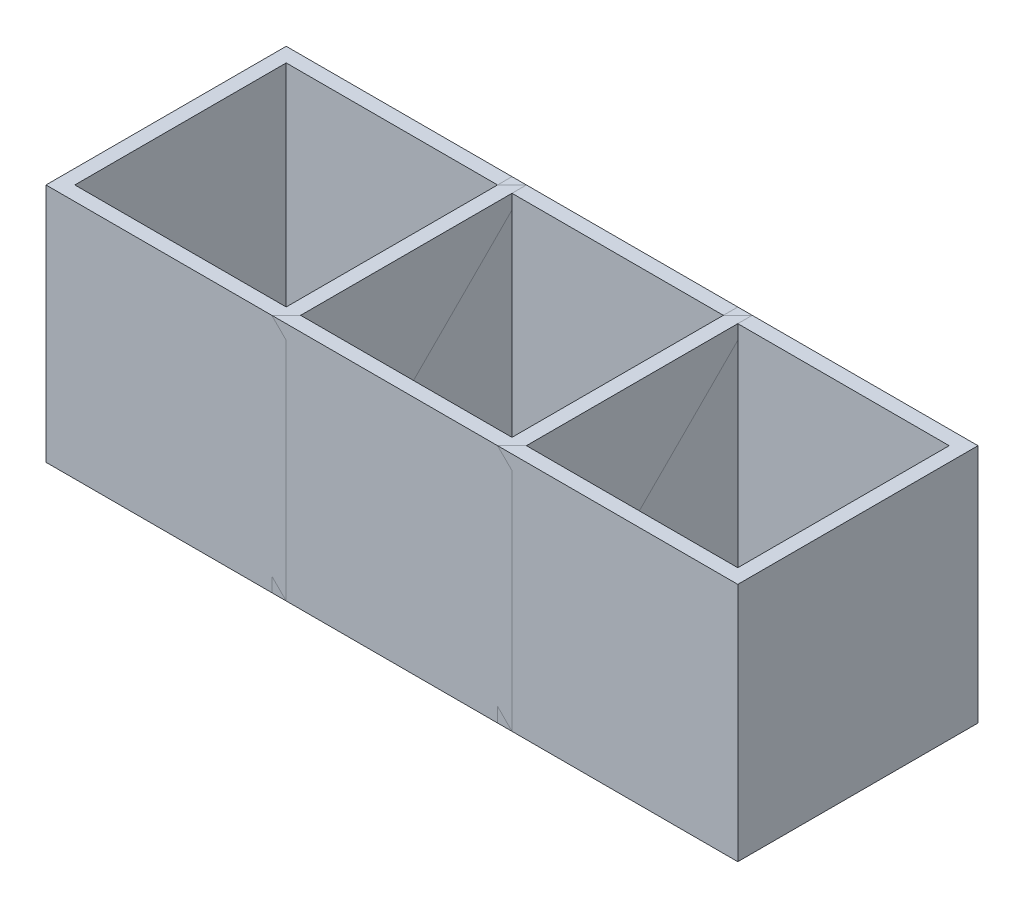
SolidWorks part; units mm, degrees
ref_plane "前基準面" through (0, 0, 0) normal (0, 0, 1) x (1, 0, 0)
ref_plane "上基準面" through (0, 0, 0) normal (0, 1, 0) x (1, 0, 0)
ref_plane "右基準面" through (0, 0, 0) normal (1, 0, 0) x (0, 0, -1)
sketch "草圖2" plane through (0, 0, 0) normal (0, 1, 0) x (1, 0, 0)
  line L13 (-25, 25) -> (25, 25)
  line L14 (-25, 25) -> (-25, -25)
  line L15 (-25, -25) -> (25, -25)
  line L16 (25, 25) -> (25, -25)
  point P4 (0, 25)
  point P5 (-25, 0)
  dimension "D1" = 50
  dimension "D2" = 50
extrude "填料-伸長1" add sketch "草圖2" along normal blind 50 contours L13 L16 L15 L14
shell "薄殼1" thickness 3
pattern_linear "直線複製排列1" count 3 spacing 47 along (1, 0, 0) of "填料-伸長1", "薄殼1"
